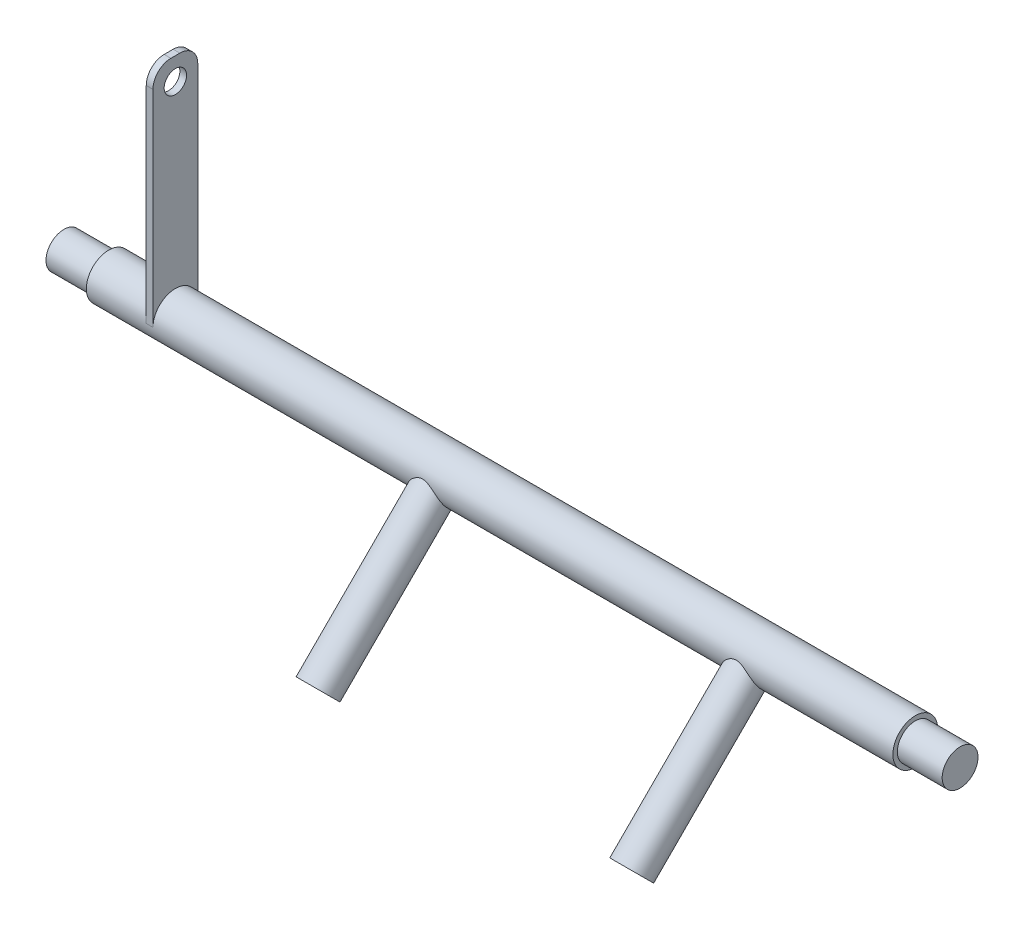
SolidWorks part; units mm, degrees
ref_plane "Front Plane" through (0, 0, 0) normal (0, 0, 1) x (1, 0, 0)
ref_plane "Top Plane" through (0, 0, 0) normal (0, 1, 0) x (1, 0, 0)
ref_plane "Right Plane" through (0, 0, 0) normal (1, 0, 0) x (0, 0, -1)
sketch "Sketch1" plane through (0, 0, 0) normal (1, 0, 0) x (0, 0, -1)
  circle A0 centre (0, 0) radius 5
extrude "Boss-Extrude1" add sketch "Sketch1" along normal blind 200
sketch "Sketch3" plane through (0, 0, 0) normal (-1, 0, 0) x (0, 0, 1)
  circle A0 centre (0, 0) radius 4
  circle A1 centre (0, 0) radius 5
extrude "Cut-Extrude1" cut sketch "Sketch3" against normal blind 10
sketch "Sketch4" plane through (200, 0, 0) normal (1, 0, 0) x (0, 0, -1)
  circle A0 centre (0, 0) radius 4
  circle A1 centre (0, 0) radius 5
extrude "Cut-Extrude2" cut sketch "Sketch4" against normal blind 10
sketch "Sketch5" plane through (0, 0, 0) normal (0, 1, 0) x (1, 0, 0)
  line L0 (10, -5) -> (190, -5) construction
  line L1 (23.3722, 5) -> (24.8722, 5)
  line L2 (23.3722, 5) -> (23.3722, -5)
  line L3 (23.3722, -5) -> (24.8722, -5)
  line L4 (24.8722, 5) -> (24.8722, -5)
  line L5 (23.3722, 5) -> (24.8722, -5) construction
  line L6 (23.3722, -5) -> (24.8722, 5) construction
  point P0 (24.1222, 0)
  dimension "D1" = 1.5
extrude "Boss-Extrude2" add sketch "Sketch5" along normal blind 50
sketch "Sketch6" plane through (23.3722, 0, 0) normal (-1, 0, 0) x (0, 0, 1)
  line L0 (-5, 50) -> (5, 50) construction
  circle A0 centre (0, 45) radius 2.5
  dimension "D1" = 5
extrude "Cut-Extrude3" cut sketch "Sketch6" against normal blind 50
fillet "Fillet1" radius 4 2 edges at (24.1222, 50, 5) (24.1222, 50, -5)
sketch "Sketch7" plane through (0, 0, 0) normal (-1, 0, 0) x (0, 0, 1)
  line L0 (0, 0) -> (0, 4) construction
  line L1 (0, 0) -> (2.8284, 2.8284) construction
  circle A0 centre (0, 0) radius 4 construction
  dimension "D1" = 45
ref_plane "Plane1" through (0, 0, 0) normal (0, 0.7071, -0.7071) x (0, 0.7071, 0.7071)
sketch "Sketch8" plane through (0, 0, 0) normal (0, 0.7071, -0.7071) x (0, 0.7071, 0.7071)
  circle A0 centre (0, 155) radius 4
  circle A1 centre (0, 85) radius 4
  point P4 (0, 0)
  dimension "D1" = 85
  dimension "D2" = 70
extrude "Boss-Extrude3" add sketch "Sketch8" against normal blind 40
